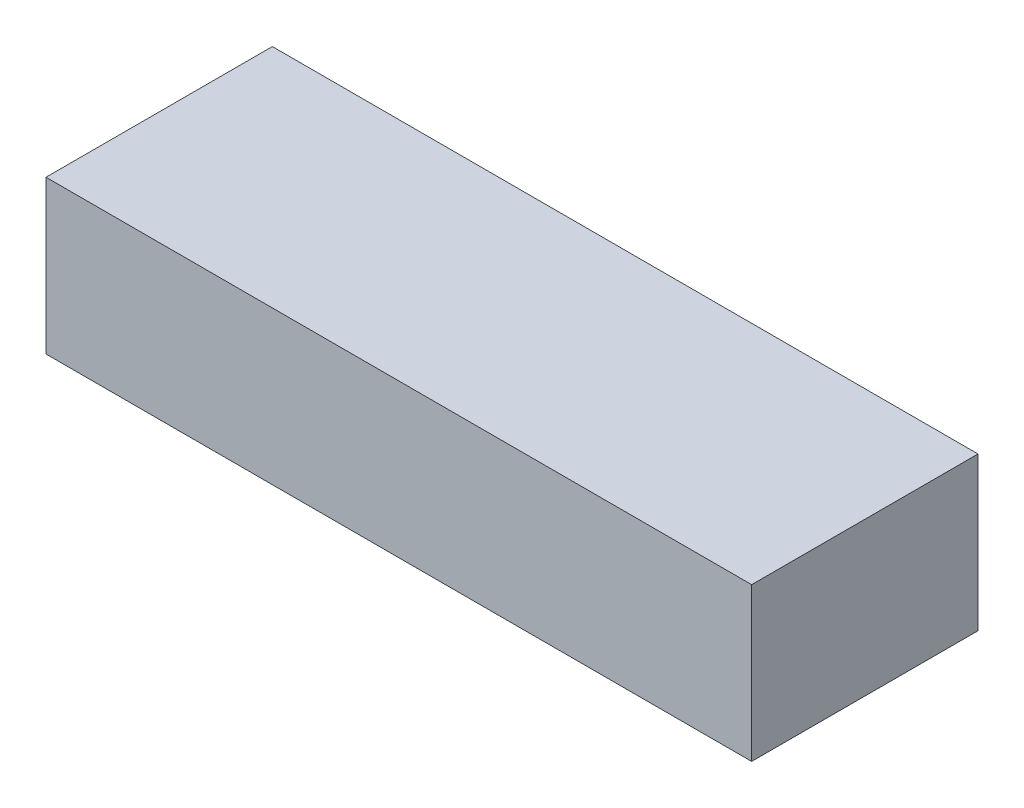
SolidWorks part; units mm, degrees
ref_plane "Front Plane" through (0, 0, 0) normal (0, 0, 1) x (1, 0, 0)
ref_plane "Top Plane" through (0, 0, 0) normal (0, 1, 0) x (1, 0, 0)
ref_plane "Right Plane" through (0, 0, 0) normal (1, 0, 0) x (0, 0, -1)
sketch "Sketch1" plane through (0, 0, 0) normal (0, 1, 0) x (1, 0, 0)
  line L1 (-53, 17) -> (53, 17)
  line L2 (-53, 17) -> (-53, -17)
  line L3 (-53, -17) -> (53, -17)
  line L4 (53, 17) -> (53, -17)
  point P0 (0, 0)
  dimension "D1" = 34
extrude "Boss-Extrude1" add sketch "Sketch1" along normal blind 23
